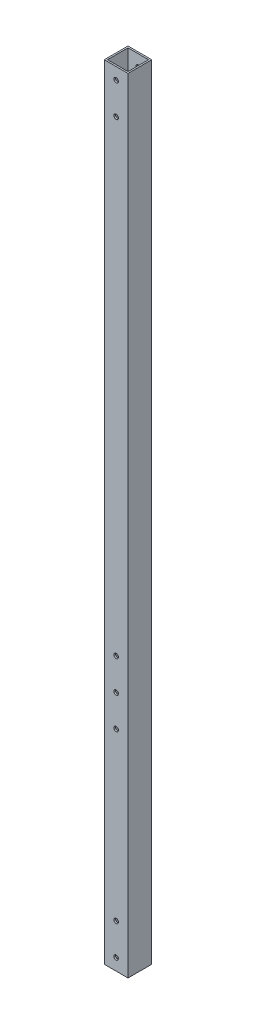
SolidWorks part; units mm, degrees
material "Thornel Mat VMA"
ref_plane "前视基准面" through (0, 0, 0) normal (0, 0, 1) x (1, 0, 0)
ref_plane "上视基准面" through (0, 0, 0) normal (0, 1, 0) x (1, 0, 0)
ref_plane "右视基准面" through (0, 0, 0) normal (1, 0, 0) x (0, 0, -1)
sketch "草图1" plane through (0, 0, 0) normal (0, 1, 0) x (1, 0, 0)
  line L1 (-7.5, -7.5) -> (7.5, -7.5)
  line L2 (-7.5, -7.5) -> (-7.5, 7.5)
  line L3 (-7.5, 7.5) -> (7.5, 7.5)
  line L4 (7.5, -7.5) -> (7.5, 7.5)
  line L5 (-7.5, -7.5) -> (7.5, 7.5) construction
  line L6 (-7.5, 7.5) -> (7.5, -7.5) construction
  point P0 (0, 0)
  dimension "D1" = 15
  dimension "D2" = 15
extrude "拉伸-薄壁1" add sketch "草图1" along normal blind 495 thin thin type one direction reverse wall 1
sketch "草图2" plane through (0, 0, 7.5) normal (0, 0, 1) x (1, 0, 0)
  line L0 (0, 0) -> (0, 495) construction
  line L1 (-7.5, 495) -> (7.5, 495) construction
  line L2 (-7.5, 0) -> (7.5, 0) construction
  circle A0 centre (0, 487.5) radius 1.45
  circle A1 centre (0, 467.5) radius 1.45
  circle A2 centre (0, 27.5) radius 1.45
  circle A3 centre (0, 7.5) radius 1.45
  circle A4 centre (0, 152.5) radius 1.45
  circle A5 centre (0, 172.5) radius 1.45
  circle A6 centre (0, 132.5) radius 1.45
  dimension "D1" = 2.9
  dimension "D3" = 20
  dimension "D5" = 20
  dimension "D6" = 20
  dimension "D7" = 20
  dimension "D2" = 7.5
  dimension "D4" = 7.5
  dimension "D8" = 125
extrude "切除-拉伸1" cut sketch "草图2" against normal through all
